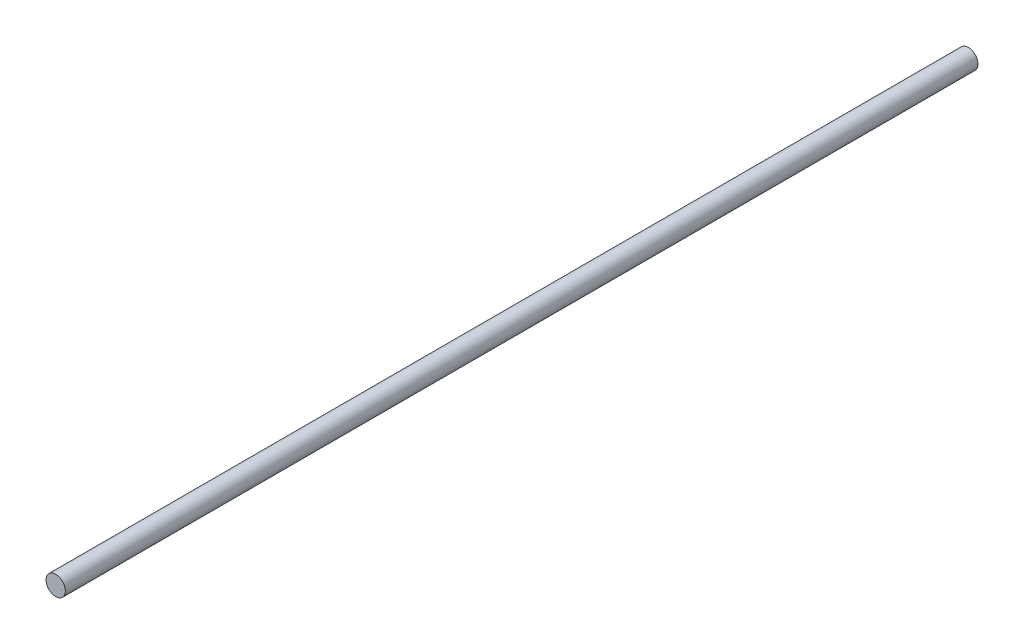
SolidWorks part; units mm, degrees
material "Простая углеродистая сталь"
ref_plane "Спереди" through (0, 0, 0) normal (0, 0, 1) x (1, 0, 0)
ref_plane "Сверху" through (0, 0, 0) normal (0, 1, 0) x (1, 0, 0)
ref_plane "Справа" through (0, 0, 0) normal (1, 0, 0) x (0, 0, -1)
sketch "Эскиз1" plane through (0, 0, 0) normal (0, 0, 1) x (1, 0, 0)
  circle A0 centre (0, 0) radius 6
  dimension "D1" = 12
extrude "Бобышка-Вытянуть1" add sketch "Эскиз1" along normal mid plane 565
